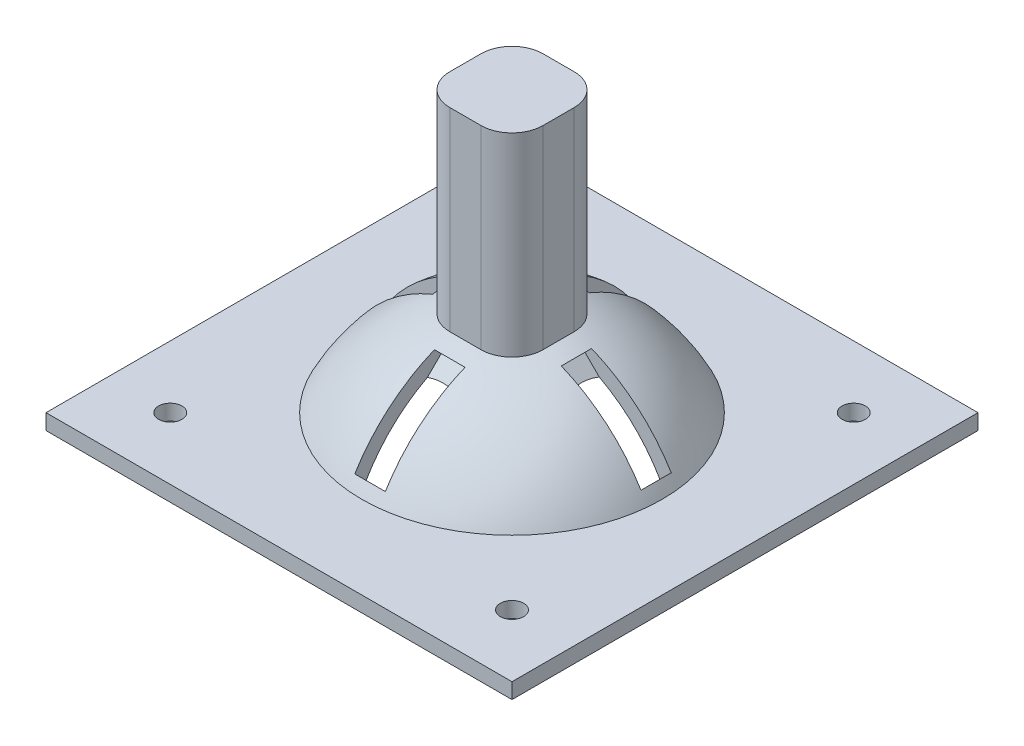
SolidWorks part; units mm, degrees
ref_plane "Front Plane" through (0, 0, 0) normal (0, 0, 1) x (1, 0, 0)
ref_plane "Top Plane" through (0, 0, 0) normal (0, 1, 0) x (1, 0, 0)
ref_plane "Right Plane" through (0, 0, 0) normal (1, 0, 0) x (0, 0, -1)
sketch "Sketch1" plane through (0, 0, 0) normal (0, 1, 0) x (1, 0, 0)
  line L1 (7.62, -7.62) -> (-7.62, -7.62)
  line L2 (7.62, -7.62) -> (7.62, 7.62)
  line L3 (7.62, 7.62) -> (-7.62, 7.62)
  line L4 (-7.62, -7.62) -> (-7.62, 7.62)
  line L5 (7.62, -7.62) -> (-7.62, 7.62) construction
  line L6 (7.62, 7.62) -> (-7.62, -7.62) construction
  point P0 (0, 0)
  dimension "D1" = 15.24
extrude "Boss-Extrude1" add sketch "Sketch1" along normal blind 31.75
fillet "Fillet1" radius 5.08 4 edges at (-7.62, 15.875, 7.62) (7.62, 15.875, 7.62) (7.62, 15.875, -7.62) (-7.62, 15.875, -7.62)
sketch "Sketch3" plane through (0, 0, 0) normal (1, 0, 0) x (0, 0, -1)
  line L2 (0, -1.2654) -> (0, -22.1401) construction
  line L3 (21.671, -13.9937) -> (24.5585, -13.9937)
  line L5 (0, -1.4651) -> (0, 1.0749)
  arc A2 (21.671, -13.9937) -> (0, -1.4651) centre (0, -26.4719) ccw
  circle A3 centre (0, -26.4719) radius 27.5468 construction
  arc A4 (24.5585, -13.9937) -> (0, 1.0749) centre (0, -26.4719) ccw
  circle A5 centre (0, -26.4719) radius 25.0068 construction
  dimension "D1" = 2.54
revolve "Revolve1" add sketch "Sketch3" angle 360 about L2
sketch "Sketch4" plane through (0, -13.9937, 0) normal (0, -1, 0) x (1, 0, 0)
  line L1 (38.1, -38.1) -> (-38.1, -38.1)
  line L2 (38.1, -38.1) -> (38.1, 38.1)
  line L3 (38.1, 38.1) -> (-38.1, 38.1)
  line L4 (-38.1, -38.1) -> (-38.1, 38.1)
  line L5 (38.1, -38.1) -> (-38.1, 38.1) construction
  line L6 (38.1, 38.1) -> (-38.1, -38.1) construction
  point P0 (0, 0)
  dimension "D1" = 76.2
extrude "Boss-Extrude2" add sketch "Sketch4" along normal blind 2.54
sketch "Sketch5" plane through (0, -16.5337, 0) normal (0, -1, 0) x (1, 0, 0)
  circle A0 centre (0, 0) radius 21.59
  dimension "D1" = 43.18
extrude "Cut-Extrude1" cut sketch "Sketch5" against normal up to surface (2.54 mm away) up to face at (0, -13.9937, 0)
sketch "Sketch6" plane through (0, -13.9937, 0) normal (0, 1, 0) x (1, 0, 0)
  line L0 (-27.94, 38.1) -> (-27.94, 27.94) construction
  line L1 (-38.1, 38.1) -> (38.1, 38.1) construction
  line L2 (-27.94, 27.94) -> (-38.1, 27.94) construction
  line L3 (-38.1, -38.1) -> (-38.1, 38.1) construction
  circle A0 centre (-27.94, 27.94) radius 1.905
  dimension "D2" = 3.81
  dimension "D1" = 10.16
extrude "Cut-Extrude2" cut sketch "Sketch6" against normal blind 2.54
pattern_linear "LPattern1" count 2 spacing 55.88 along (1, 0, 0) count 2 spacing 55.88 along (0, 0, 1) of "Cut-Extrude2"
ref_plane "Plane1" through (0, -10.8068, 10.8068) normal (0, 0.7071, -0.7071) x (-1, 0, 0)
ref_plane "Plane2" through (0, 7.1537, -7.1537) normal (0, 0.7071, -0.7071) x (-1, 0, 0)
sketch "Sketch7" plane through (0, 7.1537, -7.1537) normal (0, 0.7071, -0.7071) x (-1, 0, 0)
  line L1 (-2.309, -8.0698) -> (2.6642, -8.0698)
  line L2 (-2.309, -8.0698) -> (-2.309, -25.1207)
  line L3 (-2.309, -25.1207) -> (2.6642, -25.1207)
  line L4 (2.6642, -8.0698) -> (2.6642, -25.1207)
extrude "Cut-Extrude3" cut sketch "Sketch7" against normal blind 5.08
pattern_circular "CirPattern1" count 4 over 360 about axis through (0, 0, 0) along (0, 1, 0) of "Cut-Extrude3"
